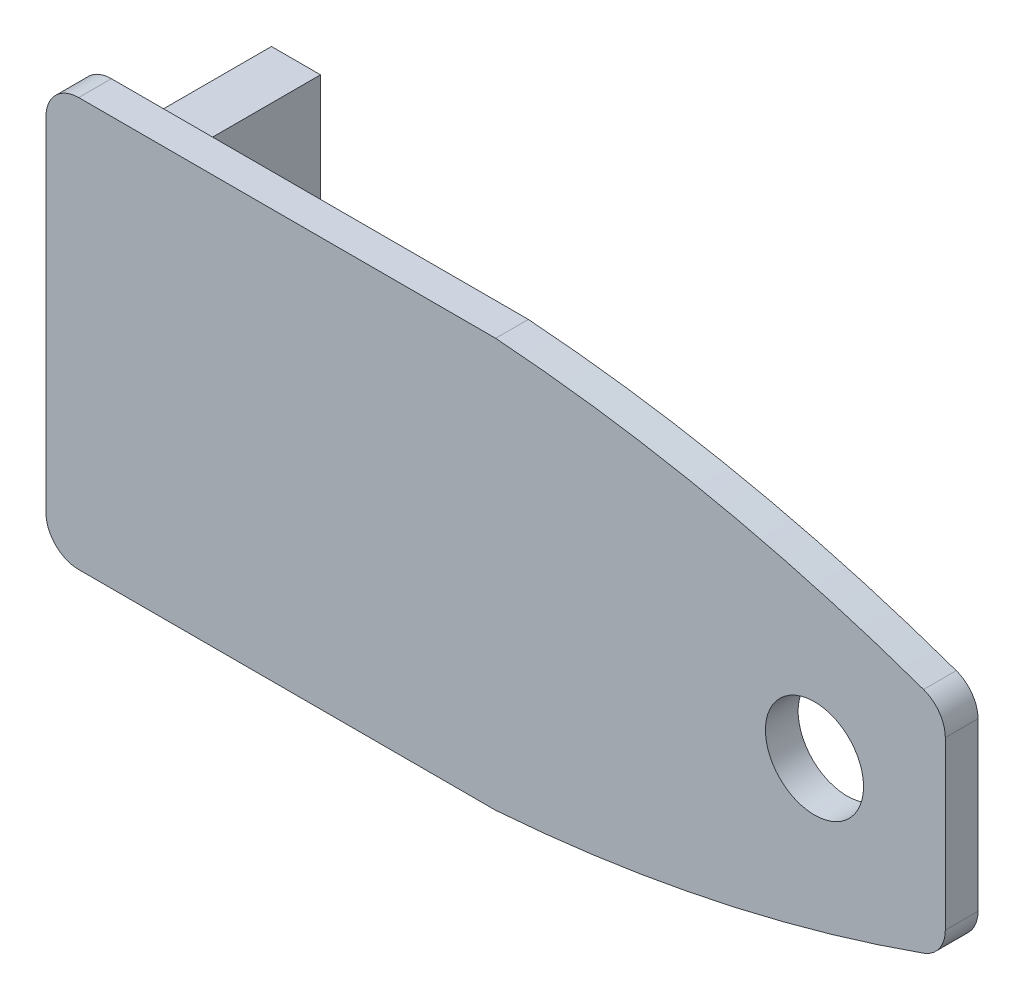
SolidWorks part; units mm, degrees
ref_plane "Front" through (0, 0, 0) normal (0, 0, 1) x (1, 0, 0)
ref_plane "Top" through (0, 0, 0) normal (0, 1, 0) x (1, 0, 0)
ref_plane "Right" through (0, 0, 0) normal (1, 0, 0) x (0, 0, -1)
sketch "Sketch1" plane through (0, 0, 0) normal (0, 0, 1) x (1, 0, 0)
  line L1 (34.925, -15.875) -> (-34.925, -15.875)
  line L2 (34.925, -15.875) -> (34.925, 15.875)
  line L3 (34.925, 15.875) -> (-34.925, 15.875)
  line L4 (-34.925, -15.875) -> (-34.925, 15.875)
  line L5 (34.925, -15.875) -> (-34.925, 15.875) construction
  line L6 (34.925, 15.875) -> (-34.925, -15.875) construction
  point P0 (0, 0)
  dimension "D1" = 31.75
  dimension "D2" = 69.85
extrude "Boss-Extrude1" add sketch "Sketch1" along normal blind 2.54
sketch "Sketch2" plane through (0, 0, 0) normal (0, 0, -1) x (-1, 0, 0)
  line L0 (1.397, 0) -> (-1.397, 0) construction
  line L1 (29.6053, -14.605) -> (25.7953, -14.605)
  line L2 (29.6053, -14.605) -> (29.6053, 14.605)
  line L3 (29.6053, 14.605) -> (25.7953, 14.605)
  line L4 (25.7953, -14.605) -> (25.7953, 14.605)
  line L5 (29.6053, -14.605) -> (25.7953, 14.605) construction
  line L6 (29.6053, 14.605) -> (25.7953, -14.605) construction
  line L7 (-34.925, 15.875) -> (34.925, 15.875) construction
  point P0 (27.7003, 0)
  dimension "D1" = 1.27
  dimension "D2" = 3.81
extrude "Boss-Extrude2" add sketch "Sketch2" along normal blind 9.652
sketch "Sketch3" plane through (-25.7953, 0, 0) normal (1, 0, 0) x (0, 0, -1)
  line L0 (9.652, 14.605) -> (9.652, -14.605) construction
  circle A0 centre (9.652, 0) radius 5.08
  dimension "D1" = 10.16
extrude "Cut-Extrude1" cut sketch "Sketch3" against normal blind 10.16
sketch "Sketch9" plane through (0, 0, 2.54) normal (0, 0, 1) x (1, 0, 0)
  line L0 (0, 15.875) -> (34.925, 15.875)
  line L1 (34.925, 15.875) -> (-34.925, 15.875) construction
  line L2 (34.925, 15.875) -> (34.925, 8.255)
  line L3 (34.925, -15.875) -> (34.925, 15.875) construction
  line L4 (0, -15.875) -> (34.925, -15.875)
  line L5 (-34.925, -15.875) -> (34.925, -15.875) construction
  line L6 (34.925, -15.875) -> (34.925, -8.255)
  arc A0 (0, 15.875) -> (34.925, 8.255) centre (-9.3403, -110.7811) cw
  arc A1 (0, -15.875) -> (34.925, -8.255) centre (-9.3403, 110.7811) ccw
  dimension "D3" = 127
  dimension "D4" = 127
  dimension "D1" = 7.62
  dimension "D2" = 7.62
extrude "Cut-Extrude2" cut sketch "Sketch9" against normal blind 10.16
fillet "Fillet1" radius 2.54 2 edges at (-34.925, -15.875, 1.27) (-34.925, 15.875, 1.27)
fillet "Fillet2" radius 2.54 2 edges at (34.925, 8.255, 1.27) (34.925, -8.255, 1.27)
sketch "Sketch11" plane through (0, 0, 2.54) normal (0, 0, 1) x (1, 0, 0)
  line L0 (6.7056, 0) -> (-6.7056, 0) construction
  line L1 (34.925, -6.4763) -> (34.925, 6.4763) construction
  circle A0 centre (24.765, 0) radius 3.81
  dimension "D1" = 7.62
  dimension "D2" = 10.16
extrude "Cut-Extrude3" cut sketch "Sketch11" against normal blind 10.16
